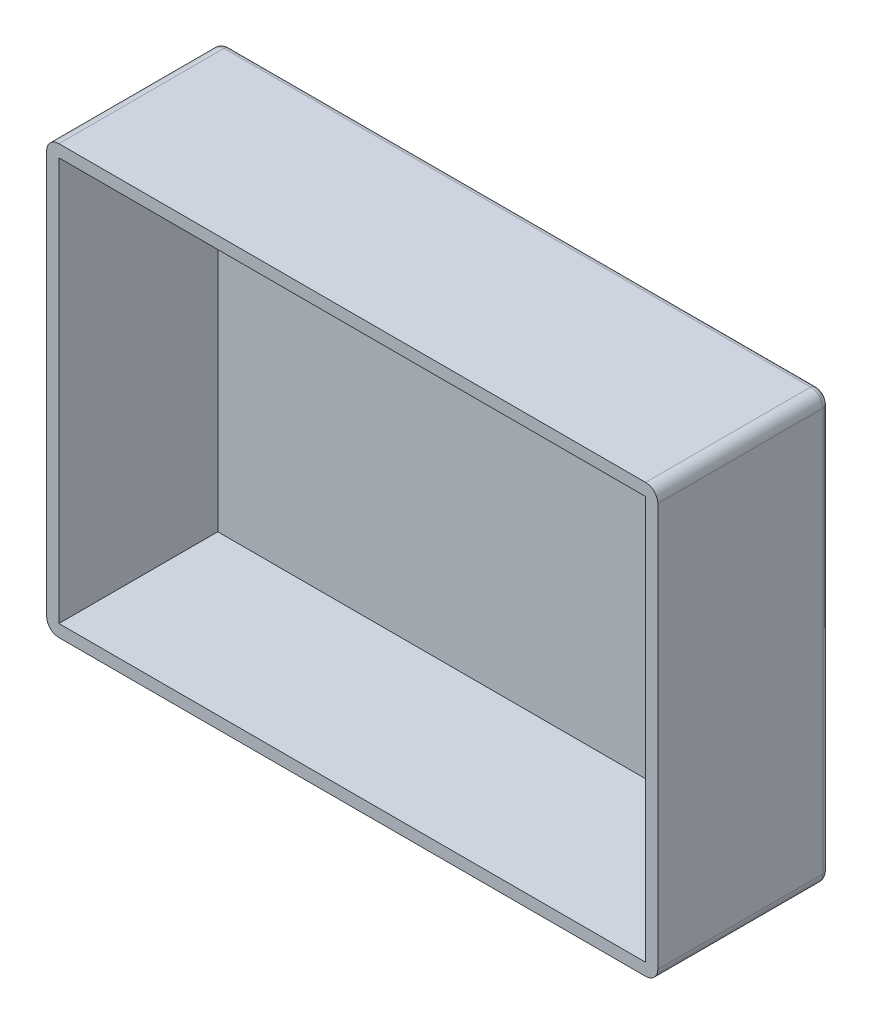
SolidWorks part; units mm, degrees
ref_plane "Front Plane" through (0, 0, 0) normal (0, 0, 1) x (1, 0, 0)
ref_plane "Top Plane" through (0, 0, 0) normal (0, 1, 0) x (1, 0, 0)
ref_plane "Right Plane" through (0, 0, 0) normal (1, 0, 0) x (0, 0, -1)
sketch "Sketch1" plane through (0, 0, 0) normal (0, 0, 1) x (1, 0, 0)
  line L1 (-250, 175) -> (250, 175)
  line L2 (-250, 175) -> (-250, -175)
  line L3 (-250, -175) -> (250, -175)
  line L4 (250, 175) -> (250, -175)
  line L5 (-250, 175) -> (250, -175) construction
  line L6 (-250, -175) -> (250, 175) construction
  point P0 (0, 0)
  dimension "D1" = 500
  dimension "D2" = 350
extrude "Boss-Extrude2" add sketch "Sketch1" along normal blind 140
sketch "Sketch4" plane through (0, 0, 140) normal (0, 0, 1) x (1, 0, 0)
  line L0 (-250, 175) -> (-250, -175) construction
  line L1 (-240, 165) -> (240, 165)
  line L2 (-240, 165) -> (-240, -165)
  line L3 (-240, -165) -> (240, -165)
  line L4 (240, 165) -> (240, -165)
  line L5 (-240, 165) -> (240, -165) construction
  line L6 (-240, -165) -> (240, 165) construction
  line L7 (250, 175) -> (-250, 175) construction
  point P0 (0, 0)
  dimension "D1" = 10
  dimension "D2" = 10
extrude "Cut-Extrude3" cut sketch "Sketch4" against normal blind 130
fillet "Fillet1" radius 10 4 edges at (250, 175, 70) (250, -175, 70) (-250, 175, 70) (-250, -175, 70)
fillet "Fillet3" radius 5 8 edges at (247.0711, 172.0711, 0) (250, 0, 0) (247.0711, -172.0711, 0) (0, -175, 0) (-247.0711, -172.0711, 0) (-250, 0, 0) (-247.0711, 172.0711, 0) (0, 175, 0)
